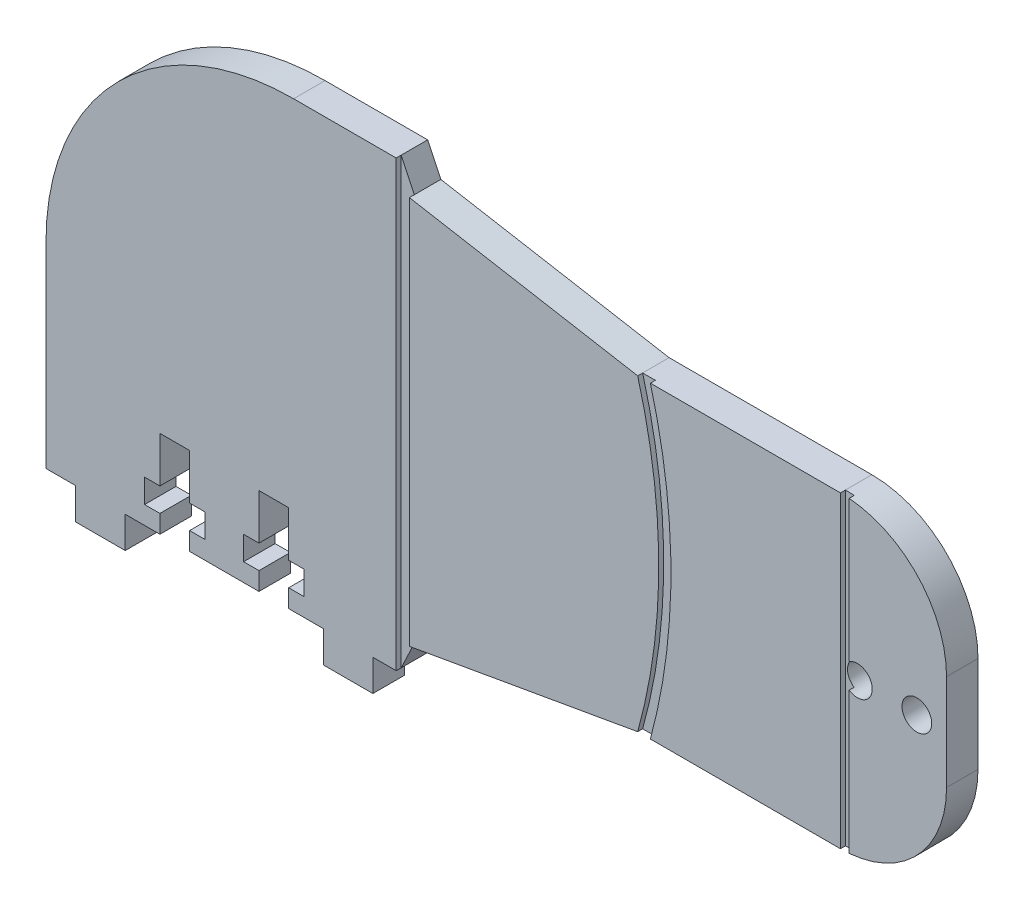
SolidWorks part; units mm, degrees
ref_plane "前视基准面" through (0, 0, 0) normal (0, 0, 1) x (1, 0, 0)
ref_plane "上视基准面" through (0, 0, 0) normal (0, 1, 0) x (1, 0, 0)
ref_plane "右视基准面" through (0, 0, 0) normal (1, 0, 0) x (0, 0, -1)
sketch "Sketch1" plane through (0, 0, 0) normal (0, 0, 1) x (1, 0, 0)
  line L0 (-343.602, 79.5824) -> (229.7313, 79.5824) construction
  line L1 (37.2968, 22.4039) -> (96.4792, 22.4039) construction
  line L7 (70.6851, 37.9618) -> (50.2151, 37.9618)
  line L8 (50.2151, 37.9618) -> (27.1662, 42.0199)
  line L9 (81.3972, 22.4039) -> (81.3972, 17.5582)
  line L11 (27.1662, 42.0199) -> (25.8378, 44.8177)
  line L12 (25.8378, 44.8177) -> (-9.5188, 44.8177)
  line L13 (81.3972, 22.4039) -> (81.3972, 27.2497)
  line L14 (27.1662, 2.788) -> (25.8378, -0.0098)
  line L15 (50.2151, 6.8461) -> (27.1662, 2.788)
  line L16 (70.6851, 6.8461) -> (50.2151, 6.8461)
  line L18 (25.8378, -0.0098) -> (-9.5188, -0.0098)
  line L20 (-9.5188, 44.8177) -> (-9.5188, -0.0098)
  arc A0 (81.3972, 27.2497) -> (70.6851, 37.9618) centre (70.6851, 27.2497) ccw
  arc A1 (81.3972, 17.5582) -> (70.6851, 6.8461) centre (70.6851, 17.5582) cw
extrude "Boss-Extrude1" add sketch "Sketch1" along normal blind 3.175
sketch "Sketch2" plane through (0, 0, 3.175) normal (0, 0, 1) x (1, 0, 0)
  line L0 (8.4812, 7.6148) -> (8.4812, -13.2615) construction
  line L1 (-4.0188, -3.1848) -> (-4.0188, 0.254) construction
  line L2 (20.9812, -3.1848) -> (20.9812, 0.254) construction
  line L3 (-9.5188, 44.8177) -> (-9.5188, -0.0098) construction
  line L4 (-6.5188, -0.0098) -> (-1.5188, -0.0098)
  line L5 (-9.5188, -0.0098) -> (25.8378, -0.0098) construction
  line L6 (-1.5188, -0.0098) -> (-1.5188, -3.1848)
  line L7 (-1.5188, -3.1848) -> (-6.5188, -3.1848)
  line L8 (-6.5188, -3.1848) -> (-6.5188, -0.0098)
  line L9 (23.4812, -3.1848) -> (23.4812, -0.0098)
  line L10 (18.4812, -3.1848) -> (23.4812, -3.1848)
  line L11 (18.4812, -0.0098) -> (18.4812, -3.1848)
  line L12 (23.4812, -0.0098) -> (18.4812, -0.0098)
  dimension "D1" = 18
  dimension "D2" = 3.175
  dimension "D3" = 5
  dimension "D4" = 25
extrude "Boss-Extrude2" add sketch "Sketch2" against normal blind 3.175
sketch "Sketch3" plane through (0, 0, 3.175) normal (0, 0, 1) x (1, 0, 0)
  line L0 (8.4812, -0.0098) -> (8.4812, 18.1235) construction
  line L1 (-1.5188, -0.0098) -> (18.4812, -0.0098) construction
  line L2 (3.4812, 5.3129) -> (3.4812, -3.9514) construction
  line L3 (4.9812, -0.0098) -> (1.9812, -0.0098)
  line L4 (1.9812, -0.0098) -> (1.9812, 1.8152)
  line L5 (1.9812, 1.8152) -> (0.4312, 1.8152)
  line L6 (0.4312, 1.8152) -> (0.4312, 4.2152)
  line L7 (0.4312, 4.2152) -> (1.9812, 4.2152)
  line L8 (1.9812, 4.2152) -> (1.9812, 8.8152)
  line L9 (1.9812, 8.8152) -> (4.9812, 8.8152)
  line L10 (4.9812, 4.2152) -> (4.9812, 8.8152)
  line L11 (6.5312, 4.2152) -> (4.9812, 4.2152)
  line L12 (6.5312, 1.8152) -> (6.5312, 4.2152)
  line L13 (4.9812, 1.8152) -> (6.5312, 1.8152)
  line L14 (4.9812, -0.0098) -> (4.9812, 1.8152)
  line L15 (-6.5188, -3.1848) -> (-1.5188, -3.1848) construction
  line L16 (13.4812, 5.3129) -> (13.4812, -3.9514) construction
  line L17 (11.9812, -0.0098) -> (11.9812, 1.8152)
  line L18 (11.9812, 1.8152) -> (10.4312, 1.8152)
  line L19 (10.4312, 1.8152) -> (10.4312, 4.2152)
  line L20 (10.4312, 4.2152) -> (11.9812, 4.2152)
  line L21 (11.9812, 4.2152) -> (11.9812, 8.8152)
  line L22 (14.9812, 8.8152) -> (11.9812, 8.8152)
  line L23 (14.9812, 4.2152) -> (14.9812, 8.8152)
  line L24 (16.5312, 4.2152) -> (14.9812, 4.2152)
  line L25 (16.5312, 1.8152) -> (16.5312, 4.2152)
  line L26 (14.9812, 1.8152) -> (16.5312, 1.8152)
  line L27 (14.9812, -0.0098) -> (14.9812, 1.8152)
  line L28 (11.9812, -0.0098) -> (14.9812, -0.0098)
  point P15 (3.4812, 8.8152)
  point P20 (3.4812, -0.0098)
  point P36 (13.4812, -0.0098)
  point P37 (13.4812, 8.8152)
  dimension "D1" = 6.1
  dimension "D2" = 2.4
  dimension "D3" = 12
  dimension "D4" = 5
  dimension "D5" = 3
  dimension "D6" = 10
extrude "Cut-Extrude1" cut sketch "Sketch3" against normal through all
sketch "Sketch4" plane through (0, 0, 3.175) normal (0, 0, 1) x (1, 0, 0)
  line L0 (81.3972, 22.4039) -> (-12.0004, 22.4039) construction
  line L1 (81.3972, 17.5582) -> (81.3972, 27.2497) construction
  line L2 (70.6851, 37.9618) -> (50.2151, 37.9618) construction
  line L3 (50.2151, 6.8461) -> (70.6851, 6.8461) construction
  line L4 (50.2151, 37.9618) -> (51.4958, 37.9618)
  line L5 (50.2151, 6.8461) -> (51.4958, 6.8461)
  line L8 (27.1662, 42.0199) -> (27.1662, 2.788)
  line L9 (25.8378, 44.8177) -> (25.8378, -0.0098)
  line L10 (27.1662, 2.788) -> (50.2151, 6.8461) construction
  line L11 (27.1662, 2.788) -> (25.8378, -0.0098)
  line L12 (25.8378, 44.8177) -> (27.1662, 42.0199)
  line L13 (70.6851, 37.9618) -> (70.6851, 6.8461)
  line L14 (71.5663, 37.9255) -> (71.5663, 6.8824)
  arc A0 (50.2151, 37.9618) -> (50.2151, 6.8461) centre (-5.5875, 22.4039) cw
  arc A1 (51.4958, 37.9618) -> (51.4958, 6.8461) centre (-5.7887, 22.4039) cw
  arc A9 (70.6851, 6.8461) -> (81.3972, 17.5582) centre (70.6851, 17.5582) ccw construction
  arc A10 (70.6851, 6.8461) -> (71.5663, 6.8824) centre (70.6851, 17.5582) ccw
  arc A11 (81.3972, 27.2497) -> (70.6851, 37.9618) centre (70.6851, 27.2497) ccw construction
  arc A12 (71.5663, 37.9255) -> (70.6851, 37.9618) centre (70.6851, 27.2497) ccw
  line M33 (25.8378, -0.0098) -> (27.1662, 2.788)
  line M41 (27.1662, 42.0199) -> (25.8378, 44.8177)
extrude "Cut-Extrude4" cut sketch "Sketch4" against normal blind 0.5 contours L0 L8 L9 M41 | L8 L0 L9 M33 | L5 A1 L4 A0 | L13 A10 L14 A12
sketch "Sketch5" plane through (0, 0, 3.175) normal (0, 0, 1) x (1, 0, 0)
  line L0 (25.8378, 44.8177) -> (-9.5188, 44.8177) construction
  line L1 (-9.5188, 44.8177) -> (-9.5188, -0.0098) construction
  line L2 (-9.5188, 44.8177) -> (15.4812, 44.8177)
  line L3 (-9.5188, 44.8177) -> (-9.5188, 19.8177)
  arc A0 (15.4812, 44.8177) -> (-9.5188, 19.8177) centre (15.4812, 19.8177) ccw
  dimension "D1" = 25
extrude "Cut-Extrude5" cut sketch "Sketch5" against normal through all
sketch "Sketch6" plane through (0, 0, 0) normal (0, 0, -1) x (-1, 0, 0)
  line L0 (-81.3972, 22.4039) -> (-60.2005, 22.4039) construction
  line L1 (-81.3972, 17.5582) -> (-81.3972, 27.2497) construction
  circle A0 centre (-78.3972, 22.4039) radius 1.5
  circle A1 centre (-72.3972, 22.4039) radius 1.5
  dimension "D1" = 3
  dimension "D2" = 3
  dimension "D3" = 6
  dimension "D4" = 3
extrude "Cut-Extrude6" cut sketch "Sketch6" against normal through all
